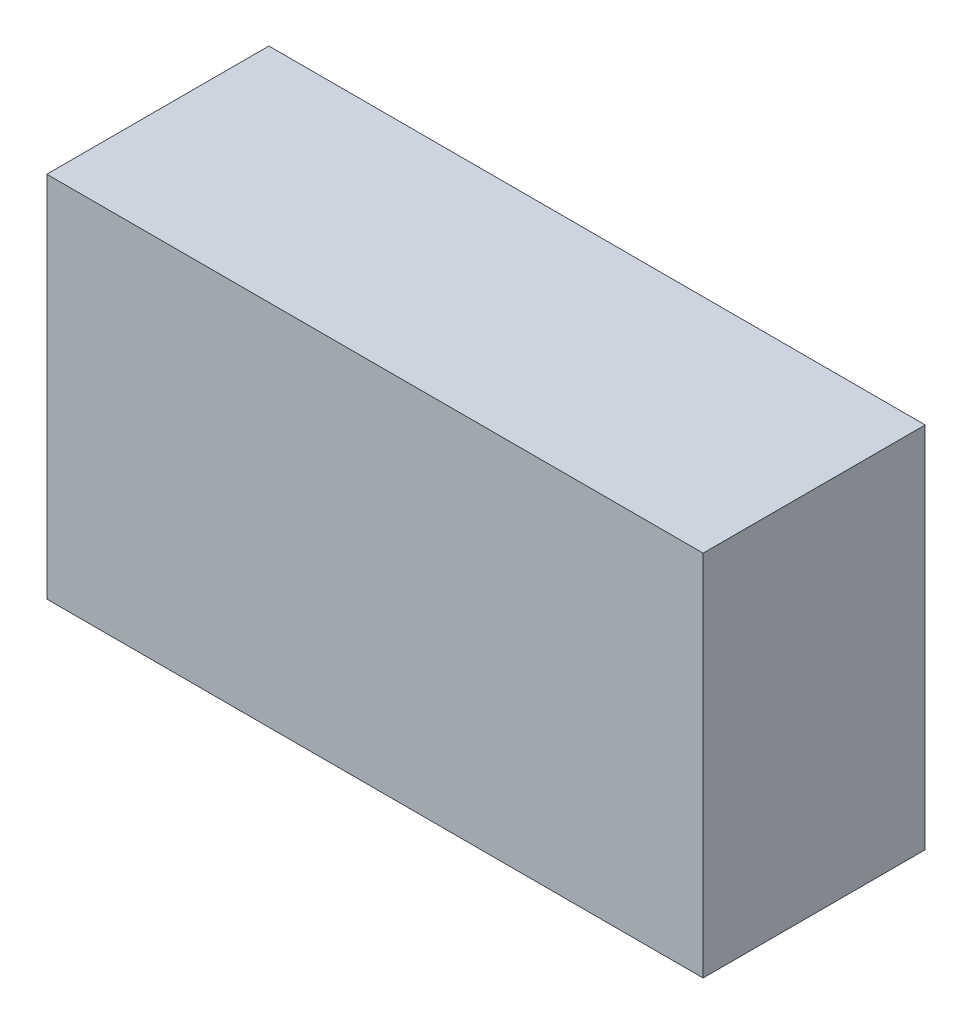
SolidWorks part; units mm, degrees
ref_plane "Front Plane" through (0, 0, 0) normal (0, 0, 1) x (1, 0, 0)
ref_plane "Top Plane" through (0, 0, 0) normal (0, 1, 0) x (1, 0, 0)
ref_plane "Right Plane" through (0, 0, 0) normal (1, 0, 0) x (0, 0, -1)
sketch "Sketch1" plane through (0, 0, 0) normal (0, 1, 0) x (1, 0, 0)
  line L0 (0, 0) -> (0, 223.3333)
  line L1 (0, 223.3333) -> (670, 223.3333)
  line L2 (670, 223.3333) -> (670, 0)
  line L3 (670, 0) -> (0, 0)
  dimension "D1" = 670
  dimension "D2" = 223.3333
extrude "Boss-Extrude1" add sketch "Sketch1" along normal blind 370
shell "Shell1" thickness 10
ref_plane "Plane1" through (660, 360, -213.3333) normal (0, -1, 0) x (-1, 0, 0)
ref_plane "Plane2" through (0, 360, -213.3333) normal (0, 0, 1) x (1, 0, 0)
sketch "Sketch5" plane through (0, 0, 0) normal (-1, 0, 0) x (0, 0, 1)
  line L6 (-5, 365) -> (-5, 5)
  line L7 (-5, 5) -> (-218.3333, 5)
  line L8 (-218.3333, 5) -> (-218.3333, 365)
  line L9 (-218.3333, 365) -> (-5, 365)
extrude "Cut-Extrude1" cut sketch "Sketch5" against normal blind 10 contours L9 L6 L7 L8
ref_plane "Plane3" through (10, 5, -218.3333) normal (0, 0, -1) x (-1, 0, 0)
ref_plane "Plane11" through (10, 365, -218.3333) normal (0, 1, 0) x (1, 0, 0)
sketch "Sketch7" plane through (0, 0, 0) normal (-1, 0, 0) x (0, 0, 1)
  line L0 (0, 0) -> (-223.3333, 0) construction
  line L1 (-111.6667, 0) -> (-111.6667, 370) construction
  line L2 (-223.3333, 370) -> (0, 370) construction
  line L4 (0, 0) -> (-223.3333, 0)
  line L5 (0, 0) -> (0, 370)
  line L6 (0, 370) -> (-223.3333, 370)
  line L7 (-223.3333, 0) -> (-223.3333, 370)
  line L8 (0, 0) -> (-223.3333, 370) construction
  line L9 (0, 370) -> (-223.3333, 0) construction
  point P8 (-111.6667, 185)
extrude "Cut-Extrude2" cut sketch "Sketch7" against normal blind 10
